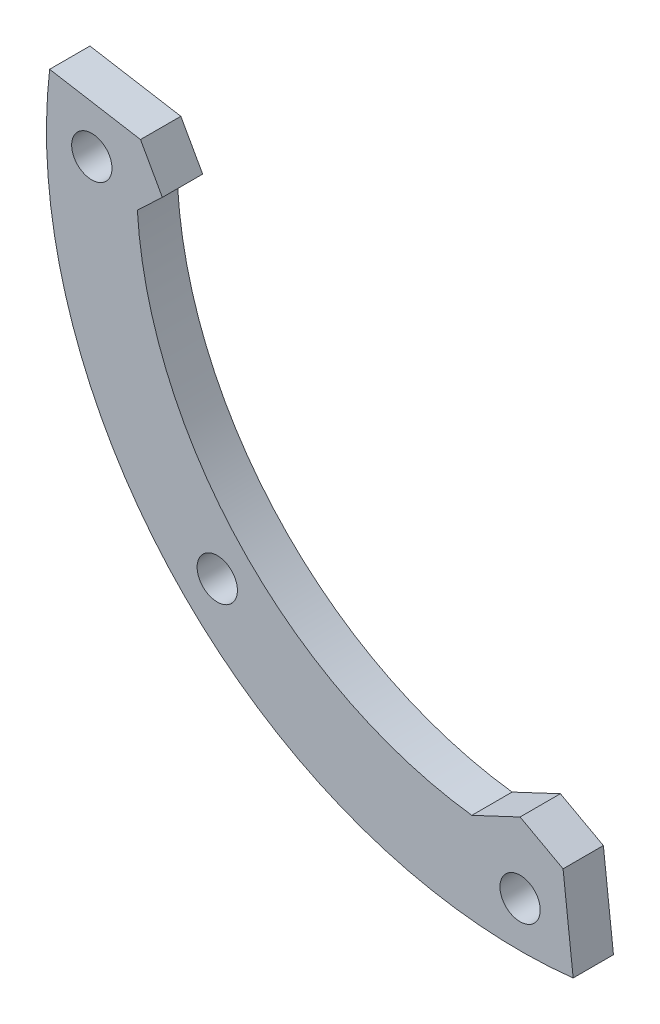
SolidWorks part; units mm, degrees
ref_plane "前视基准面" through (0, 0, 0) normal (0, 0, 1) x (1, 0, 0)
ref_plane "上视基准面" through (0, 0, 0) normal (0, 1, 0) x (1, 0, 0)
ref_plane "右视基准面" through (0, 0, 0) normal (1, 0, 0) x (0, 0, -1)
sketch "草图3" plane through (0, 0, 0) normal (0, 0, 1) x (1, 0, 0)
  line L0 (-42.5, 53.0098) -> (-35.5, 53.0098) construction
  line L1 (-37.6674, 56.8971) -> (-46.6868, 58.4263)
  line L2 (0, 17.5098) -> (-4.789, 15.2575)
  line L3 (0, 10.5098) -> (0, 17.5098) construction
  line L4 (4.2655, 15.1881) -> (0, 17.5098)
  line L7 (-37.6674, 56.8971) -> (-35.5, 53.0098)
  line L10 (0, 53.0098) -> (-33.234, 19.7758) construction
  line L13 (0, 53.0098) -> (-43.4223, 35.0237) construction
  line L14 (0, 53.0098) -> (-17.9819, 9.5857) construction
  line L20 (4.2655, 15.1881) -> (5.2673, 6.3059)
  line L22 (-35.5, 53.0098) -> (-37.9833, 50.679)
  arc A13 (5.2673, 6.3059) -> (-46.6868, 58.4263) centre (0, 53.0098) cw
  arc A14 (-37.9833, 50.679) -> (-4.789, 15.2575) centre (0, 53.0098) ccw
  circle A17 centre (0, 53.0098) radius 42.5 construction
  circle A18 centre (0, 10.5098) radius 2
  circle A19 centre (-30.052, 22.9577) radius 2
  circle A20 centre (-42.5, 53.0098) radius 2
  circle A26 centre (-30.052, 83.0618) radius 2 [skipped]
  circle A27 centre (0, 95.5098) radius 2 [skipped]
  circle A28 centre (30.052, 83.0618) radius 2 [skipped]
  circle A29 centre (42.5, 53.0098) radius 2 [skipped]
  circle A30 centre (0, 53.0098) radius 47 construction
  circle A31 centre (0, 53.0098) radius 38.0548 construction
  circle A32 centre (30.052, 22.9577) radius 2 [skipped]
  dimension "D1" = 8
extrude "凸台-拉伸1" add sketch "草图3" along normal blind 4
